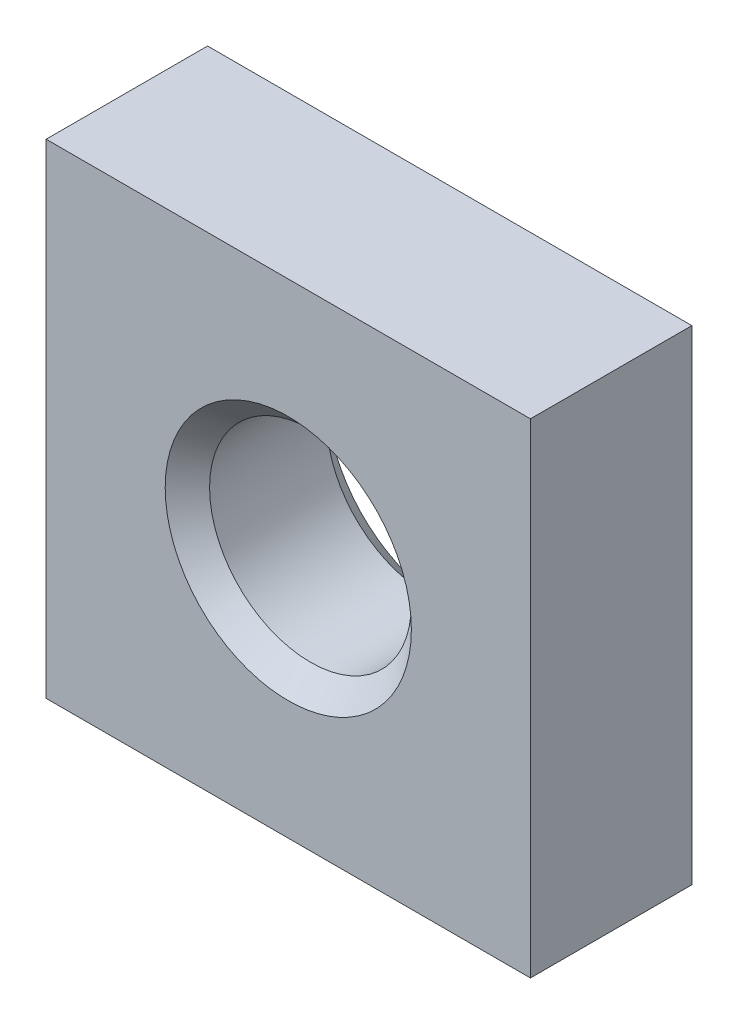
SolidWorks part; units mm, degrees
ref_plane "Front" through (0, 0, 0) normal (0, 0, 1) x (1, 0, 0)
ref_plane "Top" through (0, 0, 0) normal (0, 1, 0) x (1, 0, 0)
ref_plane "Right" through (0, 0, 0) normal (1, 0, 0) x (0, 0, -1)
sketch "草图1" plane through (0, 0, 0) normal (0, 0, 1) x (1, 0, 0)
  line L1 (-3, -3) -> (3, -3)
  line L2 (-3, -3) -> (-3, 3)
  line L3 (-3, 3) -> (3, 3)
  line L4 (3, -3) -> (3, 3)
  line L5 (-3, -3) -> (3, 3) construction
  line L6 (-3, 3) -> (3, -3) construction
  point P0 (0, 0)
  dimension "D1" = 6
  dimension "D2" = 45
extrude "凸台-拉伸1" add sketch "草图1" along normal blind 2
hole_wizard "M3 螺纹孔1" positions "草图2" profile "草图3" tap size "M3" standard "GB" end condition through all
sketch "草图2" plane through (0, 0, 2) normal (0, 0, 1) x (1, 0, 0)
  point P0 (0, 0)
sketch "草图3" plane through (0, 0, 2) normal (1, 0, 0) x (0, -1, 0)
  line L0 (0, 0) -> (0, 2)
  line L1 (0, 2) -> (1.525, 2)
  line L2 (1.25, 1.725) -> (1.25, 0.275)
  line L3 (1.25, 0.275) -> (1.525, 0)
  line L5 (1.525, 0) -> (0, 0)
  line L6 (-1.25, 0.275) -> (-1.525, 0) construction
  line L7 (1.525, 2) -> (1.25, 1.725)
  line L8 (-1.525, 2) -> (-1.25, 1.725) construction
  line L11 (0, -6.35) -> (0, 107.95) construction
  dimension "通孔螺纹孔钻头直径" = 2.5
  dimension "通孔螺纹孔钻头深度" = 2
  dimension "近端锥形沉头孔直径" = 3.05
  dimension "近端锥形沉头孔角度" = 90
  dimension "远端锥形沉头孔直径" = 3.05
  dimension "远端锥形沉头孔角度" = 90
cosmetic thread "孔螺蚊线1"
